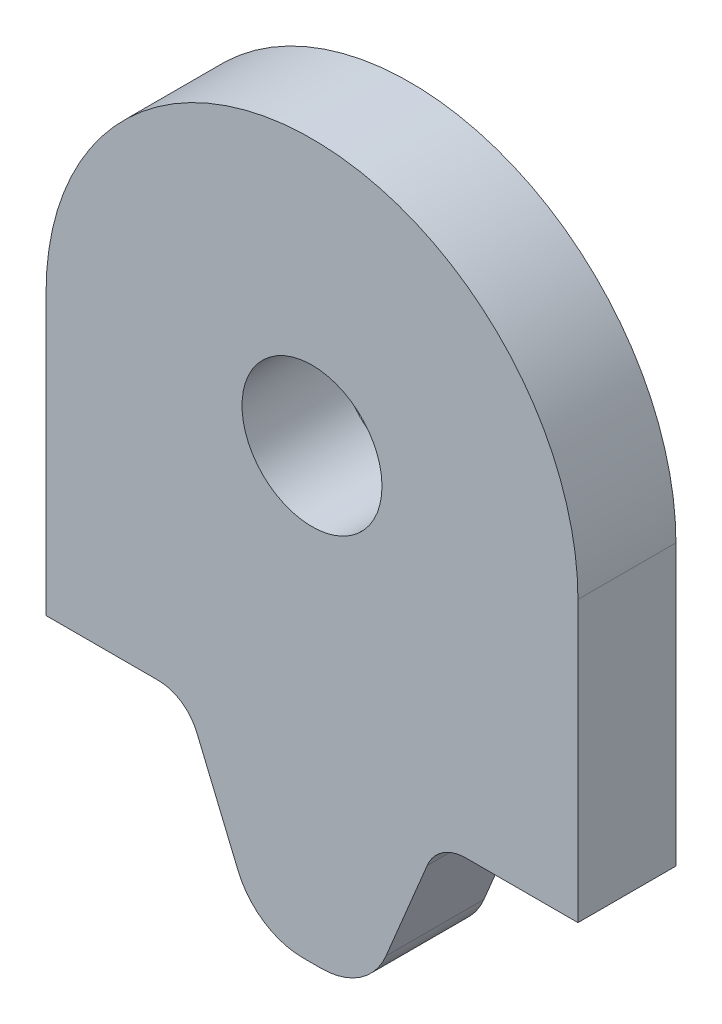
SolidWorks part; units mm, degrees
material "Foam"
ref_plane "Front Plane" through (0, 0, 0) normal (0, 0, 1) x (1, 0, 0)
ref_plane "Top Plane" through (0, 0, 0) normal (0, 1, 0) x (1, 0, 0)
ref_plane "Right Plane" through (0, 0, 0) normal (1, 0, 0) x (0, 0, -1)
sketch "Sketch1" plane through (0, 0, 0) normal (0, 0, 1) x (1, 0, 0)
  line L0 (-19, 0) -> (-19, -32)
  line L1 (-14.8, -45) -> (-5, -45)
  line L2 (19, -45) -> (19, 0)
  line L3 (0, 0) -> (0, -42) construction
  line L4 (5, -42) -> (-5, -42)
  line L5 (-5, -42) -> (-5, -45)
  line L6 (5, -42) -> (5, -45)
  line L7 (5, -45) -> (19, -45)
  line L8 (-19, -32) -> (-14.8, -32)
  line L9 (-14.8, -32) -> (-14.8, -45)
  arc A0 (19, 0) -> (-19, 0) centre (0, 0) ccw
  circle A1 centre (0, 0) radius 2.5
  arc A2 (-19, 0) -> (19, 0) centre (0, 0) ccw construction
  circle A3 centre (-14, -27) radius 1.5
  circle A6 centre (14, -27) radius 1.5
  dimension "D3" = 38
  dimension "D4" = 18
  dimension "D2" = 45
  dimension "D8" = 5
  dimension "D1" = 3
  dimension "D5" = 5
  dimension "D6" = 5
  dimension "D9" = 3
  dimension "D10" = 10
  dimension "D11" = 4.2
  dimension "D12" = 13
extrude "Boss-Extrude1" add sketch "Sketch1" along normal blind 7
sketch "Sketch2" plane through (0, 0, 7) normal (0, 0, 1) x (1, 0, 0)
  line L0 (-19, -20) -> (-9, -20)
  line L1 (-19, 0) -> (-19, -32) construction
  line L2 (-9, -20) -> (-9, -32) construction
  line L3 (-4, -32) -> (4, -32)
  line L4 (-9, -32) -> (-4, -32) construction
  line L5 (9, -20) -> (19, -20)
  line L6 (19, -45) -> (19, 0) construction
  line L7 (0, 0) -> (0, -32) construction
  line L9 (-19, -20) -> (-19, -45)
  line L10 (-19, -45) -> (19, -45)
  line L11 (19, -45) -> (19, -20)
  line L12 (-9, -20) -> (-4, -32)
  line L13 (4, -32) -> (9, -20)
  line L14 (4, -32) -> (9, -32) construction
  line L15 (9, -32) -> (9, -20) construction
  line L16 (-5, -42) -> (5, -42) construction
  circle A0 centre (0, 0) radius 5
  dimension "D1" = 10
  dimension "D2" = 12
  dimension "D3" = 10
  dimension "D4" = 10
  dimension "D5" = 5
extrude "Cut-Extrude1" cut sketch "Sketch2" against normal through all
fillet "Fillet1" radius 5 2 edges at (-4, -32, 3.5) (4, -32, 3.5)
fillet "Fillet2" radius 3 2 edges at (9, -20, 3.5) (-9, -20, 3.5)
